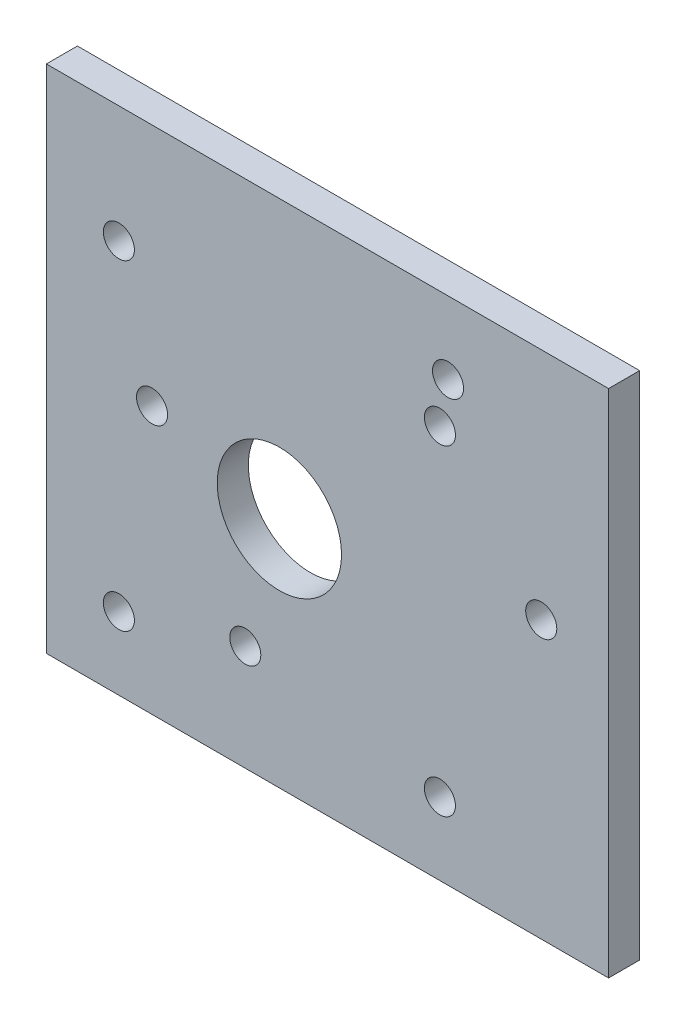
SolidWorks part; units mm, degrees
ref_plane "Front Plane" through (0, 0, 0) normal (0, 0, 1) x (1, 0, 0)
ref_plane "Top Plane" through (0, 0, 0) normal (0, 1, 0) x (1, 0, 0)
ref_plane "Right Plane" through (0, 0, 0) normal (1, 0, 0) x (0, 0, -1)
sketch "Sketch1" plane through (0, 0, 0) normal (0, 0, 1) x (1, 0, 0)
  line L1 (-22.5, 22.5) -> (22.5, 22.5)
  line L2 (-22.5, 22.5) -> (-22.5, -22.5)
  line L3 (-22.5, -22.5) -> (22.5, -22.5)
  line L4 (22.5, 22.5) -> (22.5, -22.5)
  line L5 (-22.5, 22.5) -> (22.5, -22.5) construction
  line L6 (-22.5, -22.5) -> (22.5, 22.5) construction
  circle A0 centre (0, 0) radius 6
  point P0 (0, 0)
  dimension "D1" = 12
  dimension "D2" = 45
  dimension "D3" = 45
extrude "Boss-Extrude1" add sketch "Sketch1" along normal mid plane 3
sketch "Sketch4" plane through (22.5, 0, 0) normal (1, 0, 0) x (0, 0, -1)
  line L1 (-1.5, -22.5) -> (1.5, -22.5)
  line L2 (-1.5, -22.5) -> (-1.5, 22.5)
  line L3 (-1.5, 22.5) -> (1.5, 22.5)
  line L4 (1.5, -22.5) -> (1.5, 22.5)
extrude "Boss-Extrude2" add sketch "Sketch4" along normal blind 20
sketch "Sketch2" plane through (0, 0, 1.5) normal (0, 0, 1) x (1, 0, 0)
  line L0 (0, -1.65) -> (0, 1.65) construction
  line L1 (1.65, 0) -> (-1.65, 0) construction
  circle A0 centre (-15.5, 15.5) radius 1.5
  circle A3 centre (15.5, 15.5) radius 1.5
  circle A4 centre (15.5, -15.5) radius 1.5
  circle A5 centre (-15.5, -15.5) radius 1.5
  dimension "D1" = 3
  dimension "D6" = 15.5
  dimension "D2" = 15.5
  dimension "D3" = 15.5
  dimension "D7" = 15.5
  dimension "D8" = 15.5
  dimension "D4" = 2
  dimension "D5" = 2
extrude "Cut-Extrude1" cut sketch "Sketch2" against normal mid plane 10
sketch "Sketch3" plane through (0, 0, 1.5) normal (0, 0, 1) x (1, 0, 0)
  circle A0 centre (-3.2942, -12.2942) radius 1.5
  circle A1 centre (25.2846, 4.2058) radius 1.5
  circle A2 centre (16.2846, 19.7942) radius 1.5
  circle A3 centre (-12.2942, 3.2942) radius 1.5
  circle A4 centre (-15.5, -15.5) radius 1.5 construction
  circle A5 centre (0, 0) radius 6 construction
  dimension "D1" = 3
  dimension "D8" = 12.7279
  dimension "D6" = 12.6197
  dimension "D2" = 33
  dimension "D3" = 18
  dimension "D7" = 12.7279
  dimension "D4" = 2
  dimension "D5" = 2
extrude "Cut-Extrude2" cut sketch "Sketch3" against normal mid plane 10
sketch "Sketch5" plane through (0, 22.5, 0) normal (0, 1, 0) x (1, 0, 0)
  line L1 (-22.5, -1.5) -> (42.5, -1.5)
  line L2 (-22.5, -1.5) -> (-22.5, 1.5)
  line L3 (-22.5, 1.5) -> (42.5, 1.5)
  line L4 (42.5, -1.5) -> (42.5, 1.5)
extrude "Boss-Extrude3" add sketch "Sketch5" along normal blind 4.29
sketch "Sketch6" plane through (0, 0, 1.5) normal (0, 0, 1) x (1, 0, 0)
  line L0 (-22.5, -22.5) -> (42.5, -22.5) construction
  line L1 (31.7846, -22.5) -> (42.5, -22.5)
  line L2 (31.7846, -22.5) -> (31.7846, 26.79)
  line L3 (31.7846, 26.79) -> (42.5, 26.79)
  line L4 (42.5, -22.5) -> (42.5, 26.79)
  circle A0 centre (25.2846, 4.2058) radius 1.5 construction
  dimension "D1" = 6.5
extrude "Cut-Extrude3" cut sketch "Sketch6" against normal blind 4.29
